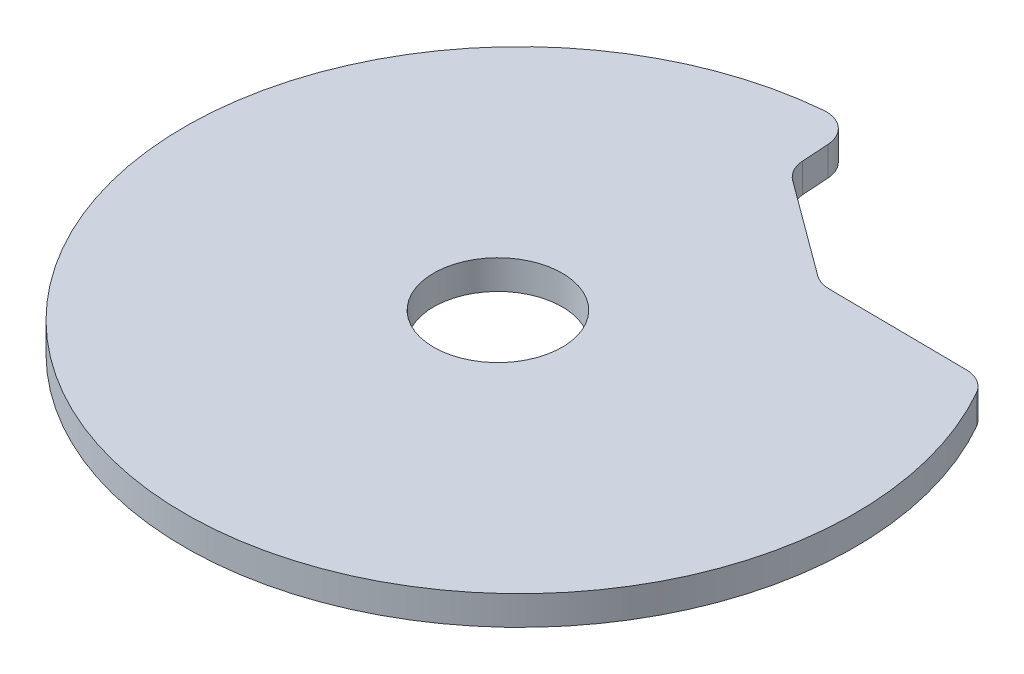
SolidWorks part; units mm, degrees
ref_plane "Спереди" through (0, 0, 0) normal (0, 0, 1) x (1, 0, 0)
ref_plane "Сверху" through (0, 0, 0) normal (0, 1, 0) x (1, 0, 0)
ref_plane "Справа" through (0, 0, 0) normal (1, 0, 0) x (0, 0, -1)
sketch "Эскиз1" plane through (0, 0, 0) normal (0, 1, 0) x (1, 0, 0)
  line L0 (110.6936, -10.706) -> (86.9871, -10.4745)
  line L1 (84.0716, -9.5012) -> (67.773, 2.498)
  line L2 (65.7479, 6.1994) -> (65.4418, 10.8965)
  arc A0 (60.0064, 15.5514) -> (114.9916, -13.2349) centre (65.1236, -41.5812) ccw
  arc A1 (110.6936, -10.706) -> (114.9916, -13.2349) centre (110.6448, -15.7058) cw
  arc A2 (84.0716, -9.5012) -> (86.9871, -10.4745) centre (87.0359, -5.4747) ccw
  arc A3 (65.7479, 6.1994) -> (67.773, 2.498) centre (70.7374, 6.5245) ccw
  arc A4 (60.0064, 15.5514) -> (65.4418, 10.8965) centre (60.4524, 10.5714) cw
  dimension "D1" = 5
extrude "Вытянуть1" add sketch "Эскиз1" along normal blind 5
sketch "Эскиз3" plane through (0, 5, 0) normal (0, 1, 0) x (1, 0, 0)
  circle A0 centre (61.7725, -41.9719) radius 11
extrude "Вырез-Вытянуть1" cut sketch "Эскиз3" against normal through all
